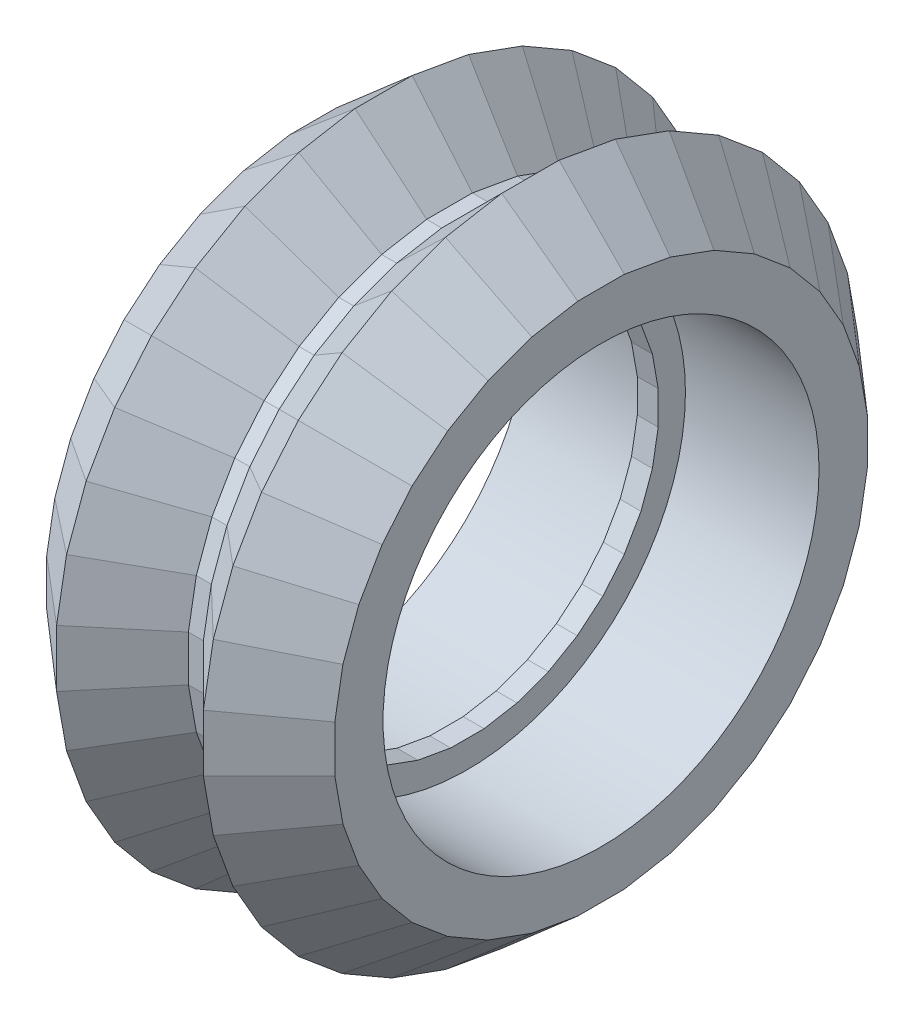
SolidWorks part; units mm, degrees
material "Chrome Stainless Steel"
ref_plane "Front Plane" through (0, 0, 0) normal (0, 0, 1) x (1, 0, 0)
ref_plane "Top Plane" through (0, 0, 0) normal (0, 1, 0) x (1, 0, 0)
ref_plane "Right Plane" through (0, 0, 0) normal (1, 0, 0) x (0, 0, -1)
sketch "Sketch1" plane through (0, 0, 0) normal (0, 0, 1) x (1, 0, 0)
  line L0 (-0.275, 9.5817) -> (0.275, 9.5817)
  line L1 (0.3833, 7) -> (0.3833, 7.5)
  line L2 (0.3833, 7.5) -> (5.0033, 7.5)
  line L3 (5.0033, 7.5) -> (5.2863, 7.783)
  line L4 (5.2863, 7.783) -> (5.2863, 9.77)
  line L5 (0.275, 9.5817) -> (2.6933, 12)
  line L6 (-0.3833, 7) -> (0.3833, 7)
  line L7 (-2.6933, 12) -> (-2.6933, 7.5) construction
  line L8 (-2.6933, 12) -> (-5.2863, 9.77)
  line L9 (2.6933, 12) -> (2.6933, 7.5) construction
  line L10 (0, 7) -> (0, 9.5817) construction
  line L11 (0, 7) -> (0, 0) construction
  line L12 (0, 0) -> (-5, 0) construction
  line L13 (-0.275, 9.5817) -> (-2.6933, 12)
  line L14 (-5.2863, 7.783) -> (-5.2863, 9.77)
  line L15 (2.6933, 12) -> (5.2863, 9.77)
  line L16 (-5.0033, 7.5) -> (-5.2863, 7.783)
  line L17 (-0.3833, 7.5) -> (-5.0033, 7.5)
  line L18 (-0.3833, 7) -> (-0.3833, 7.5)
  dimension "D2" = 90
  dimension "D3" = 3.42
  dimension "D4" = 7.5
  dimension "D5" = 0.275
  dimension "D6" = 4.62
  dimension "D7" = 135
  dimension "D8" = 12
  dimension "D9" = 9.77
  dimension "D10" = 7
  dimension "D11" = 5
sketch "Sketch2" plane through (0, 0, 0) normal (1, 0, 0) x (0, 0, -1)
  line L0 (3.1177, -11.6354) -> (5.0908, -10.9172)
  line L1 (-8.5177, -8.5177) -> (-6.9092, -9.8674)
  line L2 (-6.9092, -9.8674) -> (-5.0908, -10.9172)
  line L3 (-5.0908, -10.9172) -> (-3.1177, -11.6354)
  line L4 (-3.1177, -11.6354) -> (-1.0499, -12)
  line L5 (-1.0499, -12) -> (1.0499, -12)
  line L6 (1.0499, -12) -> (3.1177, -11.6354)
  line L7 (5.0908, -10.9172) -> (6.9092, -9.8674)
  line L8 (6.9092, -9.8674) -> (8.5177, -8.5177)
  line L9 (8.5177, -8.5177) -> (9.8674, -6.9092)
  line L10 (9.8674, -6.9092) -> (10.9172, -5.0908)
  line L11 (10.9172, -5.0908) -> (11.6354, -3.1177)
  line L12 (11.6354, -3.1177) -> (12, -1.0499)
  line L13 (12, -1.0499) -> (12, 1.0499)
  line L14 (12, 1.0499) -> (11.6354, 3.1177)
  line L15 (11.6354, 3.1177) -> (10.9172, 5.0908)
  line L16 (10.9172, 5.0908) -> (9.8674, 6.9092)
  line L17 (9.8674, 6.9092) -> (8.5177, 8.5177)
  line L18 (8.5177, 8.5177) -> (6.9092, 9.8674)
  line L19 (6.9092, 9.8674) -> (5.0908, 10.9172)
  line L20 (5.0908, 10.9172) -> (3.1177, 11.6354)
  line L21 (3.1177, 11.6354) -> (1.0499, 12)
  line L22 (1.0499, 12) -> (-1.0499, 12)
  line L23 (-1.0499, 12) -> (-3.1177, 11.6354)
  line L24 (-3.1177, 11.6354) -> (-5.0908, 10.9172)
  line L25 (-5.0908, 10.9172) -> (-6.9092, 9.8674)
  line L26 (-6.9092, 9.8674) -> (-8.5177, 8.5177)
  line L27 (-8.5177, 8.5177) -> (-9.8674, 6.9092)
  line L28 (-9.8674, 6.9092) -> (-10.9172, 5.0908)
  line L29 (-10.9172, 5.0908) -> (-11.6354, 3.1177)
  line L30 (-11.6354, 3.1177) -> (-12, 1.0499)
  line L31 (-12, 1.0499) -> (-12, -1.0499)
  line L32 (-12, -1.0499) -> (-11.6354, -3.1177)
  line L33 (-11.6354, -3.1177) -> (-10.9172, -5.0908)
  line L34 (-10.9172, -5.0908) -> (-9.8674, -6.9092)
  line L35 (-9.8674, -6.9092) -> (-8.5177, -8.5177)
  circle A0 centre (0, 0) radius 12 construction
  dimension "D1" = 24
sweep "Sweep3" add profiles "Sketch1" path "Sketch2"
sketch "Sketch3" plane through (-0.3833, 0, 0) normal (-1, 0, 0) x (0, 0, 1)
  circle A0 centre (0, 0) radius 8
  dimension "D1" = 16
sketch "Sketch4" plane through (0.3833, 0, 0) normal (1, 0, 0) x (0, 0, -1)
  circle A0 centre (0, 0) radius 8
  dimension "D1" = 16
extrude "Cut-Extrude1" cut sketch "Sketch3" along normal blind 5
extrude "Cut-Extrude2" cut sketch "Sketch4" along normal blind 5
